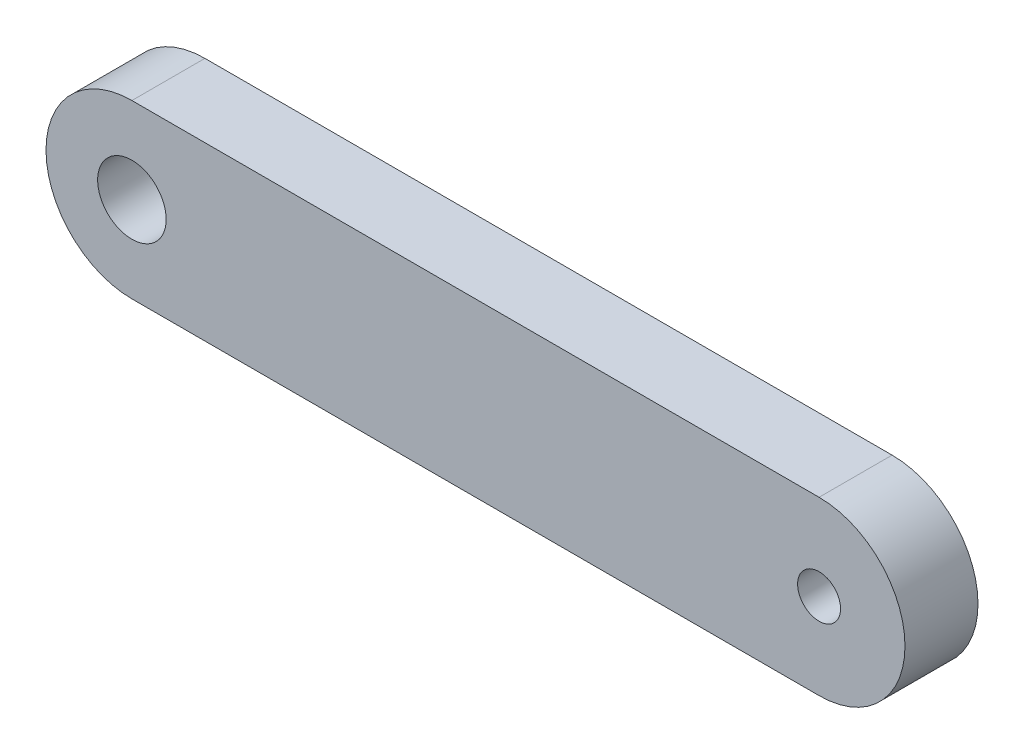
SolidWorks part; units mm, degrees
ref_plane "前视基准面" through (0, 0, 0) normal (0, 0, 1) x (1, 0, 0)
ref_plane "上视基准面" through (0, 0, 0) normal (0, 1, 0) x (1, 0, 0)
ref_plane "右视基准面" through (0, 0, 0) normal (1, 0, 0) x (0, 0, -1)
sketch "草图1" plane through (0, 0, 0) normal (0, 0, 1) x (1, 0, 0)
  line L0 (0, 0) -> (80, 0) construction
  line L1 (0, 10) -> (80, 10)
  line L2 (0, -10) -> (80, -10)
  line L3 (40, 10) -> (40, -23.9155) construction
  arc A0 (0, 10) -> (0, -10) centre (0, 0) ccw
  arc A1 (80, -10) -> (80, 10) centre (80, 0) ccw
  circle A2 centre (0, 0) radius 2.5
  circle A3 centre (80, 0) radius 2.5
  point P3 (40, 0)
  dimension "D1" = 10
  dimension "D3" = 5
  dimension "D2" = 80
extrude "凸台-拉伸1" add sketch "草图1" along normal blind 8.5
sketch "草图2" plane through (0, 0, 8.5) normal (0, 0, 1) x (1, 0, 0)
  circle A0 centre (0, 0) radius 3.987
  point P3 (15.2982, -21.6973)
  point P5 (30.0202, -0.003)
  point P6 (0, 0)
  point P7 (0.0375, -0.1093)
  dimension "D1" = 7.9741
extrude "切除-拉伸2" cut sketch "草图2" against normal through all both and the other way through all
